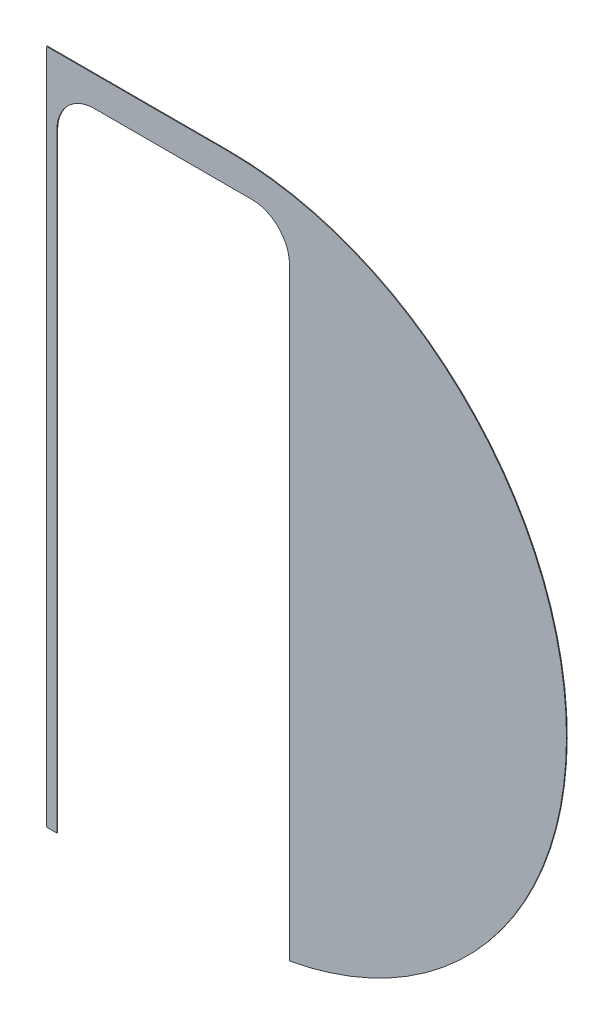
SolidWorks part; units mm, degrees
ref_plane "Front Plane" through (0, 0, 0) normal (0, 0, 1) x (1, 0, 0)
ref_plane "Top Plane" through (0, 0, 0) normal (0, 1, 0) x (1, 0, 0)
ref_plane "Right Plane" through (0, 0, 0) normal (1, 0, 0) x (0, 0, -1)
sketch "Sketch1" plane through (0, 0, 0) normal (0, 0, 1) x (1, 0, 0)
  line L1 (0, 0) -> (485, 0)
  line L2 (0, 0) -> (0, 1805)
  line L3 (0, 1805) -> (485, 1805)
  line L4 (485, 0) -> (485, 1805) construction
  arc A0 (485, 1805) -> (485, 0) centre (485, 902.5) cw
  dimension "D1" = 485
  dimension "D2" = 1805
extrude "Boss-Extrude1" add sketch "Sketch1" along normal blind 2
extrude "Cut-Extrude3" cut sketch "Sketch4" against normal blind 330
sketch "Sketch4" plane through (-1339.1121, -944.4575, 0) normal (0, 0, -1) x (-1, 0, 0)
  line L1 (-1887.1121, 819.4575) -> (-1466.1121, 819.4575)
  line L2 (-1987.1121, 919.4575) -> (-1987.1121, 2569.4575)
  line L3 (-1887.1121, 2669.4575) -> (-1466.1121, 2669.4575)
  line L4 (-1366.1121, 919.4575) -> (-1366.1121, 2569.4575)
  arc A0 (-1466.1121, 819.4575) -> (-1366.1121, 919.4575) centre (-1466.1121, 919.4575) ccw
  arc A1 (-1887.1121, 819.4575) -> (-1987.1121, 919.4575) centre (-1887.1121, 919.4575) cw
  arc A2 (-1466.1121, 2669.4575) -> (-1366.1121, 2569.4575) centre (-1466.1121, 2569.4575) cw
  arc A3 (-1987.1121, 2569.4575) -> (-1887.1121, 2669.4575) centre (-1887.1121, 2569.4575) cw
